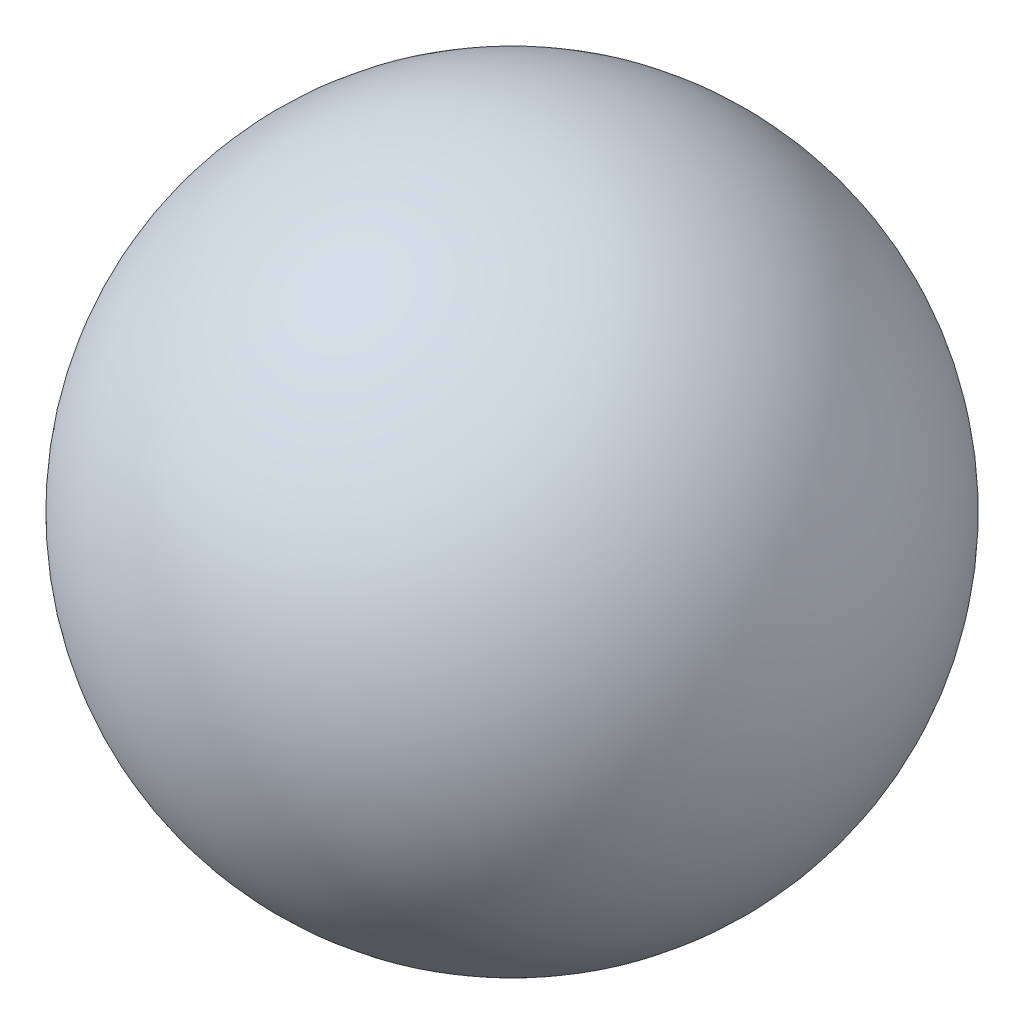
SolidWorks part; units mm, degrees
ref_plane "Front Plane" through (0, 0, 0) normal (0, 0, 1) x (1, 0, 0)
ref_plane "Top Plane" through (0, 0, 0) normal (0, 1, 0) x (1, 0, 0)
ref_plane "Right Plane" through (0, 0, 0) normal (1, 0, 0) x (0, 0, -1)
sketch "Sketch1" plane through (0, 0, 0) normal (0, 0, 1) x (1, 0, 0)
  line L0 (0, 16.9) -> (0, -16.9)
  arc A0 (0, -16.9) -> (0, 16.9) centre (0, 0) ccw
revolve "Revolve1" add sketch "Sketch1" angle 360 about L0
